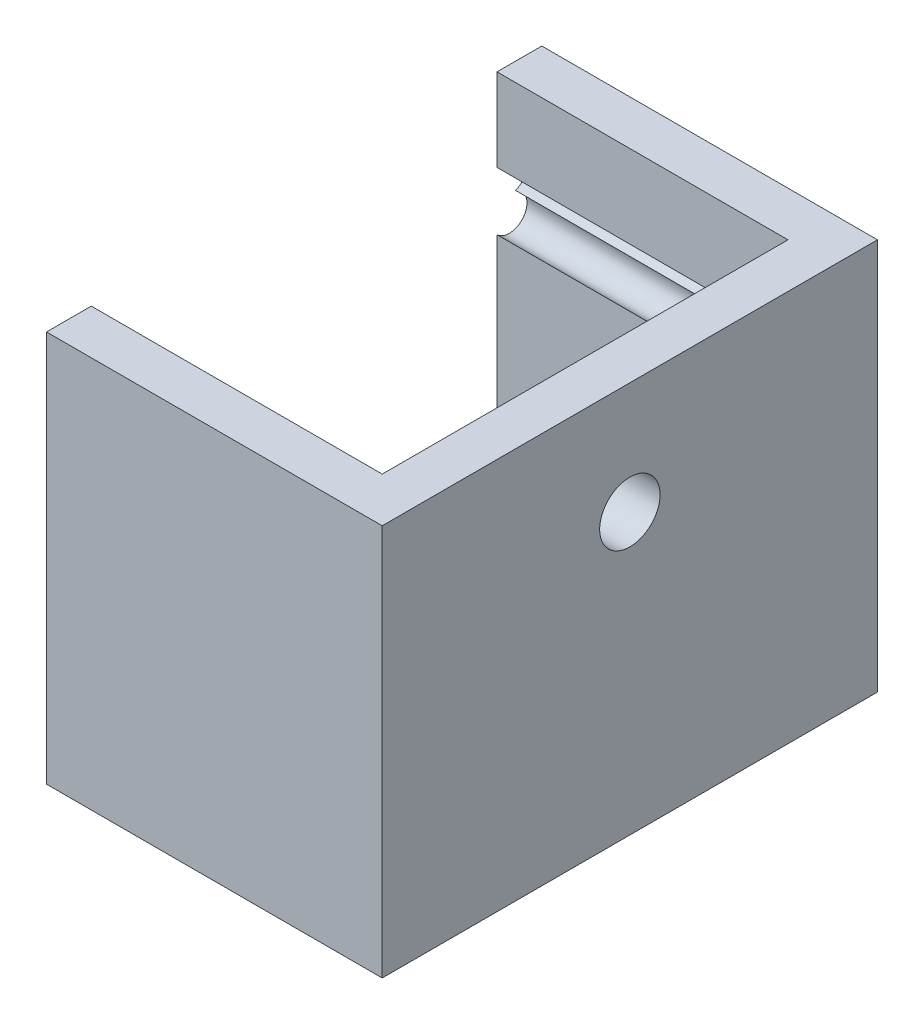
SolidWorks part; units mm, degrees
ref_plane "Front Plane" through (0, 0, 0) normal (0, 0, 1) x (1, 0, 0)
ref_plane "Top Plane" through (0, 0, 0) normal (0, 1, 0) x (1, 0, 0)
ref_plane "Right Plane" through (0, 0, 0) normal (1, 0, 0) x (0, 0, -1)
sketch "Sketch1" plane through (0, 0, 0) normal (0, 0, 1) x (1, 0, 0)
  line L1 (0, 0) -> (-30, 0)
  line L2 (0, 0) -> (0, 35)
  line L3 (0, 35) -> (-30, 35)
  line L4 (-30, 0) -> (-30, 35)
  dimension "D1" = 30
  dimension "D2" = 35
extrude "Boss-Extrude1" add sketch "Sketch1" along normal blind 44.26
sketch "Sketch2" plane through (0, 35, 0) normal (0, 1, 0) x (1, 0, 0)
  line L0 (0, -22.13) -> (-30, -22.13) construction
  line L1 (0, -44.26) -> (0, 0) construction
  line L2 (-30, -44.26) -> (-30, 0) construction
  line L3 (-30, -40.26) -> (-30, -4)
  line L4 (-30, -4) -> (-4, -4)
  line L5 (-4, -4) -> (-4, -40.26)
  line L6 (0, 0) -> (-30, 0) construction
  line L7 (-30, -40.26) -> (-4, -40.26)
  point P12 (-4, -22.13)
  dimension "D1" = 4
  dimension "D2" = 4
extrude "Cut-Extrude1" cut sketch "Sketch2" against normal blind 31
sketch "Sketch3" plane through (-30, 0, 0) normal (-1, 0, 0) x (0, 0, 1)
  line L0 (48.768, 25) -> (-14.2909, 25) construction
  line L1 (44.26, 0) -> (0, 0) construction
  line L2 (22.13, 0) -> (22.13, 35) construction
  line L3 (40.26, 35) -> (4, 35) construction
  line L5 (4, 4) -> (4, 35) construction
  line L6 (4, 4) -> (4, 35) construction
  line L7 (4, 27.6022) -> (4, 22.3978)
  line L8 (40.26, 27.6022) -> (40.26, 22.3978)
  circle A2 centre (2.9, 26.475) radius 1.575 construction
  circle A3 centre (2.9, 23.525) radius 1.575 construction
  arc A4 (4, 27.6022) -> (2.3477, 25) centre (2.9, 26.475) ccw
  arc A5 (2.3477, 25) -> (4, 22.3978) centre (2.9, 23.525) ccw
  arc A6 (40.26, 27.6022) -> (41.9123, 25) centre (41.36, 26.475) cw
  arc A7 (41.9123, 25) -> (40.26, 22.3978) centre (41.36, 23.525) cw
  dimension "D2" = 3.15
  dimension "D1" = 25
  dimension "D3" = 1.1
  dimension "D4" = 2.95
extrude "Cut-Extrude2" cut sketch "Sketch3" against normal up to surface (26 mm away) up to face at (-4, 19.5, 22.13)
sketch "Sketch4" plane through (0, 0, 0) normal (1, 0, 0) x (0, 0, -1)
  line L1 (-44.26, 0) -> (0, 0) construction
  line L2 (-22.13, 35) -> (-22.13, 0) construction
  line L3 (-44.26, 35) -> (0, 35) construction
  circle A0 centre (-22.13, 25) radius 2.7
  dimension "D2" = 5.4
  dimension "D1" = 25
extrude "Cut-Extrude3" cut sketch "Sketch4" against normal through all both and the other way through all
sketch "Sketch6" plane through (0, 4, 0) normal (0, 1, 0) x (1, 0, 0)
  line L0 (0, -44.26) -> (-30, -44.26) construction
  line L1 (-30, -4) -> (-30, -40.26) construction
  line L2 (-30, -24.26) -> (-7.8262, -24.26) construction
  circle A0 centre (-24, -34.26) radius 1.65
  circle A1 centre (-12, -34.26) radius 1.65
  circle A2 centre (-12, -14.26) radius 1.65
  circle A3 centre (-24, -14.26) radius 1.65
  dimension "D2" = 3.3
  dimension "D1" = 10
  dimension "D3" = 12
  dimension "D4" = 6
  dimension "D5" = 10
extrude "Cut-Extrude7" cut sketch "Sketch6" against normal through all both and the other way through all
equation "\"w\"= 6.9mm"
equation "\"d\"= 22mm"
equation "\"pw\"= 4mm'Part wall width"
equation "\"sdp\"= 0.58mm'Safety distance for pins"
equation "\"D1@Boss-Extrude1\"=2*\"w\"+ 2*\"pw\" + \"sdp\" + \"sdp\"+ \"d\" -0.7mm"
equation "\"D1@Sketch2\"=\"pw\""
equation "\"D2@Sketch2\"=\"pw\""
